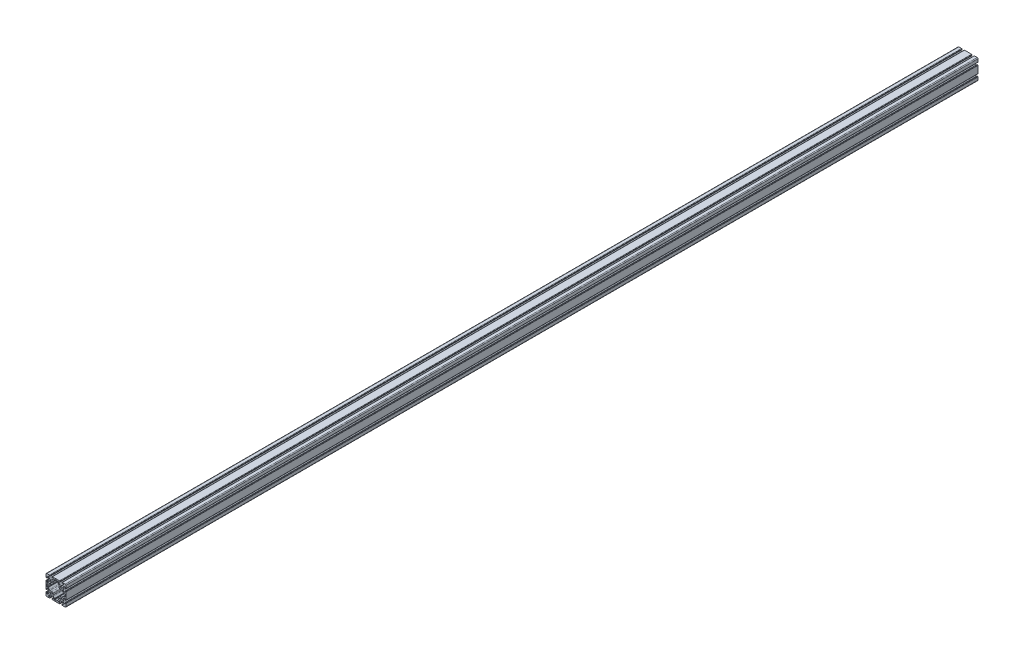
SolidWorks part; units mm, degrees
material "6061 Alloy"
ref_plane "Front Plane" through (0, 0, 0) normal (0, 0, 1) x (1, 0, 0)
ref_plane "Top Plane" through (0, 0, 0) normal (0, 1, 0) x (1, 0, 0)
ref_plane "Right Plane" through (0, 0, 0) normal (1, 0, 0) x (0, 0, -1)
sketch "Sketch1" plane through (0, 0, 0) normal (0, 0, 1) x (1, 0, 0)
  line L0 (0, -40) -> (0, 40) construction
  line L1 (0, 0) -> (-43.5804, 43.5804) construction
  line L2 (-20, 20) -> (-47.7323, 20) construction
  line L3 (-20, 20) -> (3.796, 43.796) construction
  line L4 (-20, 20) -> (-20, 43.5758) construction
  line L5 (-20, -27.7) -> (-20, -47.5576) construction
  line L131 (29.0912, 26.0365) -> (33.0827, 30.028)
  line L132 (27.7, 17.3222) -> (27.7, 22.6778)
  line L133 (29.0912, 13.9635) -> (33.0827, 9.972)
  line L134 (33.6201, 9.7494) -> (34.11, 9.7494)
  line L135 (35.68, 11.3194) -> (35.68, 14.2221)
  line L136 (37.25, 15.7921) -> (38.43, 15.7921)
  line L137 (40, 14.2221) -> (40, 7.0214)
  line L138 (40, 7.0214) -> (40, -7.0214)
  line L139 (40, -7.0214) -> (40, -14.2221)
  line L140 (38.43, -15.7921) -> (37.25, -15.7921)
  line L141 (35.68, -14.2221) -> (35.68, -11.3194)
  line L142 (33.6201, -9.7494) -> (34.11, -9.7494)
  line L143 (29.0912, -13.9635) -> (33.0827, -9.972)
  line L144 (27.7, -22.6778) -> (27.7, -17.3222)
  line L145 (29.0912, -26.0365) -> (33.0827, -30.028)
  line L146 (33.6201, -30.2506) -> (34.11, -30.2506)
  line L147 (35.68, -28.6806) -> (35.68, -25.7779)
  line L148 (37.25, -24.2079) -> (38.43, -24.2079)
  line L149 (40, -25.7779) -> (40, -33.0259)
  line L150 (40, -33.0259) -> (40, -36.83)
  line L151 (36.83, -40) -> (32.9998, -40)
  line L152 (32.9998, -40) -> (25.5696, -40)
  line L153 (23.9996, -38.43) -> (23.9996, -37.25)
  line L154 (25.5696, -35.68) -> (28.4723, -35.68)
  line L155 (30.0413, -34.0552) -> (30.0171, -33.3605)
  line L156 (29.7949, -32.8496) -> (26.0365, -29.0912)
  line L157 (17.3222, -27.7) -> (22.6778, -27.7)
  line L158 (10.035, -33.0197) -> (13.9635, -29.0912)
  line L159 (9.8124, -33.8926) -> (9.8124, -33.5571)
  line L160 (11.3824, -35.4626) -> (14.4246, -35.4626)
  line L161 (15.9946, -37.0326) -> (15.9946, -38.43)
  line L162 (14.4246, -40) -> (6.9987, -40)
  line L163 (6.9987, -40) -> (-6.9987, -40)
  line L164 (-6.9987, -40) -> (-14.4292, -40)
  line L165 (-15.9992, -38.43) -> (-15.9992, -37.25)
  line L166 (-14.4292, -35.68) -> (-11.5265, -35.68)
  line L167 (-9.9574, -34.0552) -> (-9.9816, -33.3618)
  line L168 (-10.2038, -32.8509) -> (-13.9635, -29.0912)
  line L169 (-22.6778, -27.7) -> (-17.3222, -27.7)
  line L170 (-30.028, -33.0827) -> (-26.0365, -29.0912)
  line L171 (-30.2506, -34.11) -> (-30.2506, -33.6201)
  line L172 (-28.6806, -35.68) -> (-25.7231, -35.68)
  line L173 (-24.1531, -37.25) -> (-24.1531, -38.43)
  line L174 (-25.7231, -40) -> (-33, -40)
  line L175 (-33, -40) -> (-36.83, -40)
  line L176 (-40, -36.83) -> (-40, -33.0191)
  line L177 (-40, -33.0191) -> (-40, -25.591)
  line L178 (-38.43, -24.021) -> (-37.25, -24.021)
  line L179 (-35.68, -28.4937) -> (-35.68, -25.591)
  line L180 (-34.0552, -30.0627) -> (-33.3827, -30.0392)
  line L181 (-32.8718, -29.8171) -> (-29.0912, -26.0365)
  line L182 (-27.7, -22.6778) -> (-27.7, -17.3222)
  line L183 (-29.0912, -13.9635) -> (-33.0827, -9.972)
  line L184 (-34.11, -9.7494) -> (-33.6201, -9.7494)
  line L185 (-35.68, -11.3194) -> (-35.68, -14.4473)
  line L186 (-38.43, -16.0173) -> (-37.25, -16.0173)
  line L187 (-40, -14.4473) -> (-40, -7.0169)
  line L188 (-40, -7.0169) -> (-40, 7.0169)
  line L189 (-40, 7.0169) -> (-40, 14.1348)
  line L190 (-38.1948, 15.94) -> (-36.9772, 15.94)
  line L191 (-35.68, 11.3194) -> (-35.68, 14.6428)
  line L192 (-34.11, 9.7494) -> (-33.6201, 9.7494)
  line L193 (-33.0827, 9.972) -> (-29.0912, 13.9635)
  line L194 (-27.7, 17.3222) -> (-27.7, 22.6778)
  line L195 (-29.0912, 26.0365) -> (-33.0827, 30.028)
  line L196 (-34.11, 30.2506) -> (-33.6201, 30.2506)
  line L197 (-35.68, 28.6806) -> (-35.68, 25.3572)
  line L198 (-38.1948, 24.06) -> (-36.9772, 24.06)
  line L199 (-40, 25.8652) -> (-40, 33.3181)
  line L200 (-40, 33.3181) -> (-40, 36.83)
  line L201 (-36.83, 40) -> (-33.0314, 40)
  line L202 (-33.0314, 40) -> (-25.8652, 40)
  line L203 (-24.06, 36.9772) -> (-24.06, 38.1948)
  line L204 (-25.3572, 35.68) -> (-28.7018, 35.68)
  line L205 (-30.285, 33.6069) -> (-30.285, 34.0968)
  line L206 (-30.0961, 33.1508) -> (-26.0365, 29.0912)
  line L207 (-22.6778, 27.7) -> (-17.3222, 27.7)
  line L208 (-13.9635, 29.0912) -> (-9.9039, 33.1508)
  line L209 (-9.715, 33.6069) -> (-9.715, 34.0968)
  line L210 (-14.6428, 35.68) -> (-11.2982, 35.68)
  line L211 (-15.94, 36.9772) -> (-15.94, 38.1948)
  line L212 (-14.1348, 40) -> (-6.9844, 40)
  line L213 (-6.9844, 40) -> (6.9844, 40)
  line L214 (6.9844, 40) -> (14.1348, 40)
  line L215 (15.94, 36.9772) -> (15.94, 38.1948)
  line L216 (14.6428, 35.68) -> (11.2982, 35.68)
  line L217 (9.715, 33.6069) -> (9.715, 34.0968)
  line L218 (9.9039, 33.1508) -> (13.9635, 29.0912)
  line L219 (17.3222, 27.7) -> (22.6778, 27.7)
  line L220 (26.0365, 29.0912) -> (30.028, 33.0827)
  line L221 (30.2506, 33.6201) -> (30.2506, 34.11)
  line L222 (25.5409, 35.679) -> (28.6258, 35.679)
  line L223 (23.9709, 37.249) -> (23.9709, 38.43)
  line L224 (25.5409, 40) -> (36.83, 40)
  line L226 (40, 36.83) -> (40, 32.9339)
  line L227 (40, 32.9339) -> (40, 25.7779)
  line L228 (38.43, 24.2079) -> (37.0956, 24.2079)
  line L229 (35.5256, 25.7779) -> (35.5256, 28.6806)
  line L230 (33.6201, 30.2506) -> (33.9556, 30.2506)
  line L231 (17.07, 12.32) -> (22.6578, 12.32)
  line L232 (26.0165, 10.9288) -> (31.1439, 5.8014)
  line L233 (32.0419, 5.4294) -> (34.41, 5.4294)
  line L234 (35.68, -4.1594) -> (35.68, 4.1594)
  line L235 (32.0419, -5.4294) -> (34.41, -5.4294)
  line L236 (26.0165, -10.9288) -> (31.1439, -5.8014)
  line L237 (17.07, -12.32) -> (22.6578, -12.32)
  line L238 (12.32, -22.6578) -> (12.32, -17.07)
  line L239 (5.8014, -31.1439) -> (10.9288, -26.0165)
  line L240 (5.4294, -34.41) -> (5.4294, -32.0419)
  line L241 (-4.1594, -35.68) -> (4.1594, -35.68)
  line L242 (-5.4294, -34.41) -> (-5.4294, -32.0419)
  line L243 (-5.8014, -31.1439) -> (-10.9288, -26.0165)
  line L244 (-12.32, -22.6578) -> (-12.32, -17.07)
  line L245 (-22.6578, -12.32) -> (-17.07, -12.32)
  line L246 (-26.0165, -10.9288) -> (-31.1439, -5.8014)
  line L247 (-34.41, -5.4294) -> (-32.0419, -5.4294)
  line L248 (-35.68, -4.1594) -> (-35.68, 4.1594)
  line L249 (-34.41, 5.4294) -> (-32.0419, 5.4294)
  line L250 (-31.1439, 5.8014) -> (-26.0165, 10.9288)
  line L251 (-22.6578, 12.32) -> (-17.07, 12.32)
  line L252 (-12.32, 17.07) -> (-12.32, 22.6578)
  line L253 (-10.9288, 26.0165) -> (-5.8014, 31.1439)
  line L254 (-5.4294, 32.0419) -> (-5.4294, 34.41)
  line L255 (-4.1594, 35.68) -> (4.1594, 35.68)
  line L256 (5.4294, 32.0419) -> (5.4294, 34.41)
  line L257 (5.8014, 31.1439) -> (10.9288, 26.0165)
  line L258 (12.32, 17.07) -> (12.32, 22.6578)
  line L260 (-40, 0) -> (40, 0) construction
  circle A116 centre (-20, 20) radius 3.4
  circle A117 centre (20, 20) radius 3.4
  circle A118 centre (20, -20) radius 3.4
  circle A119 centre (-20, -20) radius 3.4
  arc A120 (29.0912, 26.0365) -> (27.7, 22.6778) centre (32.45, 22.6778) ccw
  arc A121 (27.7, 17.3222) -> (29.0912, 13.9635) centre (32.45, 17.3222) ccw
  arc A122 (33.0827, 9.972) -> (33.6201, 9.7494) centre (33.6201, 10.5094) ccw
  arc A123 (34.11, 9.7494) -> (35.68, 11.3194) centre (34.11, 11.3194) ccw
  arc A124 (37.25, 15.7921) -> (35.68, 14.2221) centre (37.25, 14.2221) ccw
  arc A125 (40, 14.2221) -> (38.43, 15.7921) centre (38.43, 14.2221) ccw
  arc A126 (38.43, -15.7921) -> (40, -14.2221) centre (38.43, -14.2221) ccw
  arc A127 (35.68, -14.2221) -> (37.25, -15.7921) centre (37.25, -14.2221) ccw
  arc A128 (35.68, -11.3194) -> (34.11, -9.7494) centre (34.11, -11.3194) ccw
  arc A129 (33.6201, -9.7494) -> (33.0827, -9.972) centre (33.6201, -10.5094) ccw
  arc A130 (29.0912, -13.9635) -> (27.7, -17.3222) centre (32.45, -17.3222) ccw
  arc A131 (27.7, -22.6778) -> (29.0912, -26.0365) centre (32.45, -22.6778) ccw
  arc A132 (33.0827, -30.028) -> (33.6201, -30.2506) centre (33.6201, -29.4906) ccw
  arc A133 (34.11, -30.2506) -> (35.68, -28.6806) centre (34.11, -28.6806) ccw
  arc A134 (37.25, -24.2079) -> (35.68, -25.7779) centre (37.25, -25.7779) ccw
  arc A135 (40, -25.7779) -> (38.43, -24.2079) centre (38.43, -25.7779) ccw
  arc A136 (36.83, -40) -> (40, -36.83) centre (36.83, -36.83) ccw
  arc A137 (23.9996, -38.43) -> (25.5696, -40) centre (25.5696, -38.43) ccw
  arc A138 (25.5696, -35.68) -> (23.9996, -37.25) centre (25.5696, -37.25) ccw
  arc A139 (28.4723, -35.68) -> (30.0413, -34.0552) centre (28.4723, -34.11) ccw
  arc A140 (30.0171, -33.3605) -> (29.7949, -32.8496) centre (29.2575, -33.387) ccw
  arc A141 (26.0365, -29.0912) -> (22.6778, -27.7) centre (22.6778, -32.45) ccw
  arc A142 (17.3222, -27.7) -> (13.9635, -29.0912) centre (17.3222, -32.45) ccw
  arc A143 (10.035, -33.0197) -> (9.8124, -33.5571) centre (10.5724, -33.5571) ccw
  arc A144 (9.8124, -33.8926) -> (11.3824, -35.4626) centre (11.3824, -33.8926) ccw
  arc A145 (15.9946, -37.0326) -> (14.4246, -35.4626) centre (14.4246, -37.0326) ccw
  arc A146 (14.4246, -40) -> (15.9946, -38.43) centre (14.4246, -38.43) ccw
  arc A147 (-15.9992, -38.43) -> (-14.4292, -40) centre (-14.4292, -38.43) ccw
  arc A148 (-14.4292, -35.68) -> (-15.9992, -37.25) centre (-14.4292, -37.25) ccw
  arc A149 (-11.5265, -35.68) -> (-9.9574, -34.0552) centre (-11.5265, -34.11) ccw
  arc A150 (-9.9816, -33.3618) -> (-10.2038, -32.8509) centre (-10.7412, -33.3883) ccw
  arc A151 (-13.9635, -29.0912) -> (-17.3222, -27.7) centre (-17.3222, -32.45) ccw
  arc A152 (-22.6778, -27.7) -> (-26.0365, -29.0912) centre (-22.6778, -32.45) ccw
  arc A153 (-30.028, -33.0827) -> (-30.2506, -33.6201) centre (-29.4906, -33.6201) ccw
  arc A154 (-30.2506, -34.11) -> (-28.6806, -35.68) centre (-28.6806, -34.11) ccw
  arc A155 (-24.1531, -37.25) -> (-25.7231, -35.68) centre (-25.7231, -37.25) ccw
  arc A156 (-25.7231, -40) -> (-24.1531, -38.43) centre (-25.7231, -38.43) ccw
  arc A157 (-40, -36.83) -> (-36.83, -40) centre (-36.83, -36.83) ccw
  arc A158 (-38.43, -24.021) -> (-40, -25.591) centre (-38.43, -25.591) ccw
  arc A159 (-35.68, -25.591) -> (-37.25, -24.021) centre (-37.25, -25.591) ccw
  arc A160 (-35.68, -28.4937) -> (-34.0552, -30.0627) centre (-34.11, -28.4937) ccw
  arc A161 (-33.3827, -30.0392) -> (-32.8718, -29.8171) centre (-33.4092, -29.2797) ccw
  arc A162 (-29.0912, -26.0365) -> (-27.7, -22.6778) centre (-32.45, -22.6778) ccw
  arc A163 (-27.7, -17.3222) -> (-29.0912, -13.9635) centre (-32.45, -17.3222) ccw
  arc A164 (-33.0827, -9.972) -> (-33.6201, -9.7494) centre (-33.6201, -10.5094) ccw
  arc A165 (-34.11, -9.7494) -> (-35.68, -11.3194) centre (-34.11, -11.3194) ccw
  arc A166 (-37.25, -16.0173) -> (-35.68, -14.4473) centre (-37.25, -14.4473) ccw
  arc A167 (-40, -14.4473) -> (-38.43, -16.0173) centre (-38.43, -14.4473) ccw
  arc A168 (-38.1948, 15.94) -> (-40, 14.1348) centre (-38.1948, 14.1348) ccw
  arc A169 (-35.68, 14.6428) -> (-36.9772, 15.94) centre (-36.9772, 14.6428) ccw
  arc A170 (-35.68, 11.3194) -> (-34.11, 9.7494) centre (-34.11, 11.3194) ccw
  arc A171 (-33.6201, 9.7494) -> (-33.0827, 9.972) centre (-33.6201, 10.5094) ccw
  arc A172 (-29.0912, 13.9635) -> (-27.7, 17.3222) centre (-32.45, 17.3222) ccw
  arc A173 (-27.7, 22.6778) -> (-29.0912, 26.0365) centre (-32.45, 22.6778) ccw
  arc A174 (-33.0827, 30.028) -> (-33.6201, 30.2506) centre (-33.6201, 29.4906) ccw
  arc A175 (-34.11, 30.2506) -> (-35.68, 28.6806) centre (-34.11, 28.6806) ccw
  arc A176 (-36.9772, 24.06) -> (-35.68, 25.3572) centre (-36.9772, 25.3572) ccw
  arc A177 (-40, 25.8652) -> (-38.1948, 24.06) centre (-38.1948, 25.8652) ccw
  arc A178 (-36.83, 40) -> (-40, 36.83) centre (-36.83, 36.83) ccw
  arc A179 (-24.06, 38.1948) -> (-25.8652, 40) centre (-25.8652, 38.1948) ccw
  arc A180 (-25.3572, 35.68) -> (-24.06, 36.9772) centre (-25.3572, 36.9772) ccw
  arc A181 (-28.7018, 35.68) -> (-30.285, 34.0968) centre (-28.7018, 34.0968) ccw
  arc A182 (-30.285, 33.6069) -> (-30.0961, 33.1508) centre (-29.6399, 33.6069) ccw
  arc A183 (-26.0365, 29.0912) -> (-22.6778, 27.7) centre (-22.6778, 32.45) ccw
  arc A184 (-17.3222, 27.7) -> (-13.9635, 29.0912) centre (-17.3222, 32.45) ccw
  arc A185 (-9.9039, 33.1508) -> (-9.715, 33.6069) centre (-10.3601, 33.6069) ccw
  arc A186 (-9.715, 34.0968) -> (-11.2982, 35.68) centre (-11.2982, 34.0968) ccw
  arc A187 (-15.94, 36.9772) -> (-14.6428, 35.68) centre (-14.6428, 36.9772) ccw
  arc A188 (-14.1348, 40) -> (-15.94, 38.1948) centre (-14.1348, 38.1948) ccw
  arc A189 (15.94, 38.1948) -> (14.1348, 40) centre (14.1348, 38.1948) ccw
  arc A190 (14.6428, 35.68) -> (15.94, 36.9772) centre (14.6428, 36.9772) ccw
  arc A191 (11.2982, 35.68) -> (9.715, 34.0968) centre (11.2982, 34.0968) ccw
  arc A192 (9.715, 33.6069) -> (9.9039, 33.1508) centre (10.3601, 33.6069) ccw
  arc A193 (13.9635, 29.0912) -> (17.3222, 27.7) centre (17.3222, 32.45) ccw
  arc A194 (22.6778, 27.7) -> (26.0365, 29.0912) centre (22.6778, 32.45) ccw
  arc A195 (30.028, 33.0827) -> (30.2506, 33.6201) centre (29.4906, 33.6201) ccw
  arc A196 (30.2506, 34.11) -> (28.6258, 35.679) centre (28.6806, 34.11) ccw
  arc A197 (23.9709, 37.249) -> (25.5409, 35.679) centre (25.5409, 37.249) ccw
  arc A198 (25.5409, 40) -> (23.9709, 38.43) centre (25.5409, 38.43) ccw
  arc A199 (40, 36.83) -> (36.83, 40) centre (36.83, 36.83) ccw
  arc A200 (38.43, 24.2079) -> (40, 25.7779) centre (38.43, 25.7779) ccw
  arc A201 (35.5256, 25.7779) -> (37.0956, 24.2079) centre (37.0956, 25.7779) ccw
  arc A202 (35.5256, 28.6806) -> (33.9556, 30.2506) centre (33.9556, 28.6806) ccw
  arc A203 (33.6201, 30.2506) -> (33.0827, 30.028) centre (33.6201, 29.4906) ccw
  arc A204 (26.0165, 10.9288) -> (22.6578, 12.32) centre (22.6578, 7.57) ccw
  arc A205 (31.1439, 5.8014) -> (32.0419, 5.4294) centre (32.0419, 6.6994) ccw
  arc A206 (35.68, 4.1594) -> (34.41, 5.4294) centre (34.41, 4.1594) ccw
  arc A207 (34.41, -5.4294) -> (35.68, -4.1594) centre (34.41, -4.1594) ccw
  arc A208 (32.0419, -5.4294) -> (31.1439, -5.8014) centre (32.0419, -6.6994) ccw
  arc A209 (22.6578, -12.32) -> (26.0165, -10.9288) centre (22.6578, -7.57) ccw
  arc A210 (17.07, -12.32) -> (12.32, -17.07) centre (17.07, -17.07) ccw
  arc A211 (10.9288, -26.0165) -> (12.32, -22.6578) centre (7.57, -22.6578) ccw
  arc A212 (5.8014, -31.1439) -> (5.4294, -32.0419) centre (6.6994, -32.0419) ccw
  arc A213 (4.1594, -35.68) -> (5.4294, -34.41) centre (4.1594, -34.41) ccw
  arc A214 (-5.4294, -34.41) -> (-4.1594, -35.68) centre (-4.1594, -34.41) ccw
  arc A215 (-5.4294, -32.0419) -> (-5.8014, -31.1439) centre (-6.6994, -32.0419) ccw
  arc A216 (-12.32, -22.6578) -> (-10.9288, -26.0165) centre (-7.57, -22.6578) ccw
  arc A217 (-12.32, -17.07) -> (-17.07, -12.32) centre (-17.07, -17.07) ccw
  arc A218 (-26.0165, -10.9288) -> (-22.6578, -12.32) centre (-22.6578, -7.57) ccw
  arc A219 (-31.1439, -5.8014) -> (-32.0419, -5.4294) centre (-32.0419, -6.6994) ccw
  arc A220 (-35.68, -4.1594) -> (-34.41, -5.4294) centre (-34.41, -4.1594) ccw
  arc A221 (-34.41, 5.4294) -> (-35.68, 4.1594) centre (-34.41, 4.1594) ccw
  arc A222 (-32.0419, 5.4294) -> (-31.1439, 5.8014) centre (-32.0419, 6.6994) ccw
  arc A223 (-22.6578, 12.32) -> (-26.0165, 10.9288) centre (-22.6578, 7.57) ccw
  arc A224 (-17.07, 12.32) -> (-12.32, 17.07) centre (-17.07, 17.07) ccw
  arc A225 (-10.9288, 26.0165) -> (-12.32, 22.6578) centre (-7.57, 22.6578) ccw
  arc A226 (-5.8014, 31.1439) -> (-5.4294, 32.0419) centre (-6.6994, 32.0419) ccw
  arc A227 (-4.1594, 35.68) -> (-5.4294, 34.41) centre (-4.1594, 34.41) ccw
  arc A228 (5.4294, 34.41) -> (4.1594, 35.68) centre (4.1594, 34.41) ccw
  arc A229 (5.4294, 32.0419) -> (5.8014, 31.1439) centre (6.6994, 32.0419) ccw
  arc A230 (12.32, 22.6578) -> (10.9288, 26.0165) centre (7.57, 22.6578) ccw
  arc A231 (12.32, 17.07) -> (17.07, 12.32) centre (17.07, 17.07) ccw
  dimension "D8" = 6.8
  dimension "D1" = 80
  dimension "D2" = 40
  dimension "D3" = 20
  dimension "D4" = 20.57
  dimension "D5" = 4.32
  dimension "D6" = 4.32
  dimension "D7" = 8.12
  dimension "D9" = 4.32
  dimension "D10" = 12.3
extrude "Extrude1" add sketch "Sketch1" against normal blind 3657.6
